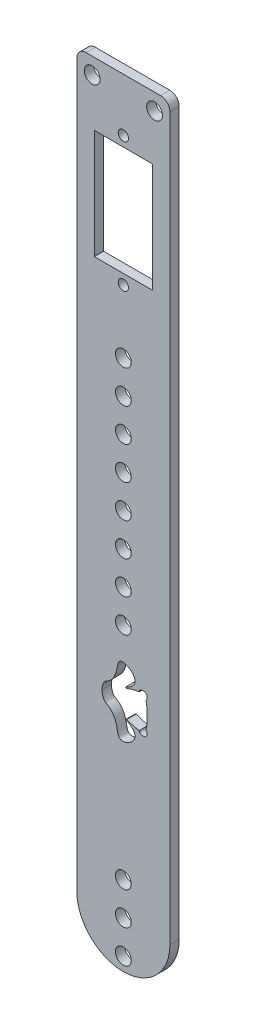
SolidWorks part; units mm, degrees
ref_plane "前视基准面" through (0, 0, 0) normal (0, 0, 1) x (1, 0, 0)
ref_plane "上视基准面" through (0, 0, 0) normal (0, 1, 0) x (1, 0, 0)
ref_plane "右视基准面" through (0, 0, 0) normal (1, 0, 0) x (0, 0, -1)
other "Configuration Table"
sketch "草图3" plane through (0, 0, 0) normal (0, 0, 1) x (1, 0, 0)
  line L0 (0.8408, 56.1176) -> (16.8408, 56.1176)
  line L1 (18.8408, 54.1176) -> (18.8408, -100.8824)
  line L3 (-1.1592, -100.8824) -> (-1.1592, 54.1176)
  line L4 (8.8408, 54.093) -> (8.8408, -48.1016) construction
  line L5 (15.0908, 42.5383) -> (2.5908, 42.5383)
  line L6 (2.5908, 42.5383) -> (2.5908, 19.0383)
  line L7 (15.0908, 42.5383) -> (15.0908, 19.0383)
  line L8 (2.5908, 19.0383) -> (15.0908, 19.0383)
  line L9 (2.5908, 30.7883) -> (20.6308, 30.7883) construction
  line L12 (18.8408, 56.1176) -> (-1.1592, 56.1176)
  line L14 (8.8408, -92.0824) -> (8.8408, -176.6957) construction
  line L15 (8.8408, -92.0824) -> (8.8408, -48.1016) construction
  circle A0 centre (8.8408, -107.9824) radius 1.7
  circle A1 centre (8.8408, -100.8824) radius 1.7
  circle A2 centre (8.8408, -93.7824) radius 1.7
  circle A3 centre (2.1408, 52.6176) radius 1.7
  circle A4 centre (15.5408, 52.6176) radius 1.7
  circle A5 centre (8.8408, 44.6883) radius 1.1
  circle A6 centre (8.8408, 16.8883) radius 1.1
  circle A15 centre (8.8408, -32.2016) radius 1.7
  circle A16 centre (8.8408, -18.0016) radius 1.7
  circle A17 centre (8.8408, -25.1016) radius 1.7
  circle A18 centre (8.8408, -39.3016) radius 1.7
  circle A19 centre (8.8408, -10.9016) radius 1.7
  circle A20 centre (8.8408, -3.8016) radius 1.7
  circle A21 centre (8.8408, 3.2984) radius 1.7
  circle A22 centre (8.8408, -46.4016) radius 1.7
  arc A23 (-1.1592, -100.8824) -> (18.8408, -100.8824) centre (8.8408, -100.8824) ccw
  arc A24 (16.8408, 56.1176) -> (18.8408, 54.1176) centre (16.8408, 54.1176) cw
  arc A25 (0.8408, 56.1176) -> (-1.1592, 54.1176) centre (0.8408, 54.1176) ccw
  spline S0 degree 3 poles (4.278, -60.7046) (4.2266, -61.1572) (4.5342, -62.2856) (4.9358, -62.6454) (5.0043, -62.6757) knots 0 0 0 0 0.481577 0.579603 0.579603 0.579603 0.579603
  spline S1 degree 3 poles (4.9754, -62.6611) (6.6661, -63.5088) (7.3572, -65.149) (8.0209, -69.7285) (13.9129, -65.7161) (9.3247, -63.7251) knots 0 0 0 0 0.410927 0.553507 1 1 1 1
  spline S2 degree 2 poles (9.3247, -63.7251) (9.4484, -63.6677) (9.5794, -63.5839) knots 0.879374 0.879374 0.879374 1 1 1
  spline S3 degree 3 poles (9.5794, -63.5839) (10.4428, -63.937) (11.3351, -64.1758) (12.2564, -64.3004) knots 0 0 0 0 0.985819 0.985819 0.985819 0.985819
  spline S4 degree 3 poles (12.2564, -64.3004) (12.2504, -64.3917) (12.324, -64.9577) (14.135, -65.1249) (14.0276, -63.753) (13.6979, -63.4688) knots 0.192176 0.192176 0.192176 0.192176 0.262472 0.642904 1 1 1 1
  spline S5 degree 2 poles (13.6979, -63.4688) (14.0148, -62.1014) (13.928, -60.7046) knots 0 0 0 1 1 1
  spline S6 degree 2 poles (13.6979, -57.9405) (14.0148, -59.3079) (13.928, -60.7046) knots 0 0 0 1 1 1
  spline S7 degree 3 poles (12.2564, -57.1089) (12.2504, -57.0176) (12.324, -56.4516) (14.135, -56.2844) (14.0276, -57.6563) (13.6979, -57.9405) knots 0.192176 0.192176 0.192176 0.192176 0.262472 0.642904 1 1 1 1
  spline S8 degree 3 poles (9.5794, -57.8254) (10.4428, -57.4723) (11.3351, -57.2335) (12.2564, -57.1089) knots 0 0 0 0 0.985819 0.985819 0.985819 0.985819
  spline S9 degree 2 poles (9.3247, -57.6842) (9.4484, -57.7416) (9.5794, -57.8254) knots 0.879374 0.879374 0.879374 1 1 1
  spline S10 degree 3 poles (4.9754, -58.7481) (6.6661, -57.9005) (7.3572, -56.2603) (8.0209, -51.6808) (13.9129, -55.6932) (9.3247, -57.6842) knots 0 0 0 0 0.410927 0.553507 1 1 1 1
  spline S11 degree 3 poles (4.278, -60.7046) (4.2266, -60.2521) (4.5342, -59.1237) (4.9358, -58.7639) (5.0043, -58.7336) knots 0 0 0 0 0.481577 0.579603 0.579603 0.579603 0.579603
  point P10 (8.8408, 42.5383)
  point P27 (18.8408, 56.1176)
  point P30 (-1.1592, 56.1176)
  point P48 (0, 0)
  point P49 (0, 0)
  dimension "D3" = 7.1
  dimension "D5" = 13.4
  dimension "D8" = 27.8
  dimension "D9" = 3.5
  dimension "D10" = 2
  dimension "D2" = 20
  dimension "D4" = 7.1
  dimension "D6" = 12.5
  dimension "D7" = 23.5
  dimension "D13" = 10
  dimension "D18" = 7.1
  dimension "D19" = 7.1
  dimension "D20" = 7.1
  dimension "D21" = 7.1
  dimension "D22" = 7.1
  dimension "D23" = 7.1
  dimension "D24" = 7.1
extrude "凸台-拉伸2" add sketch "草图3" along normal blind 2
